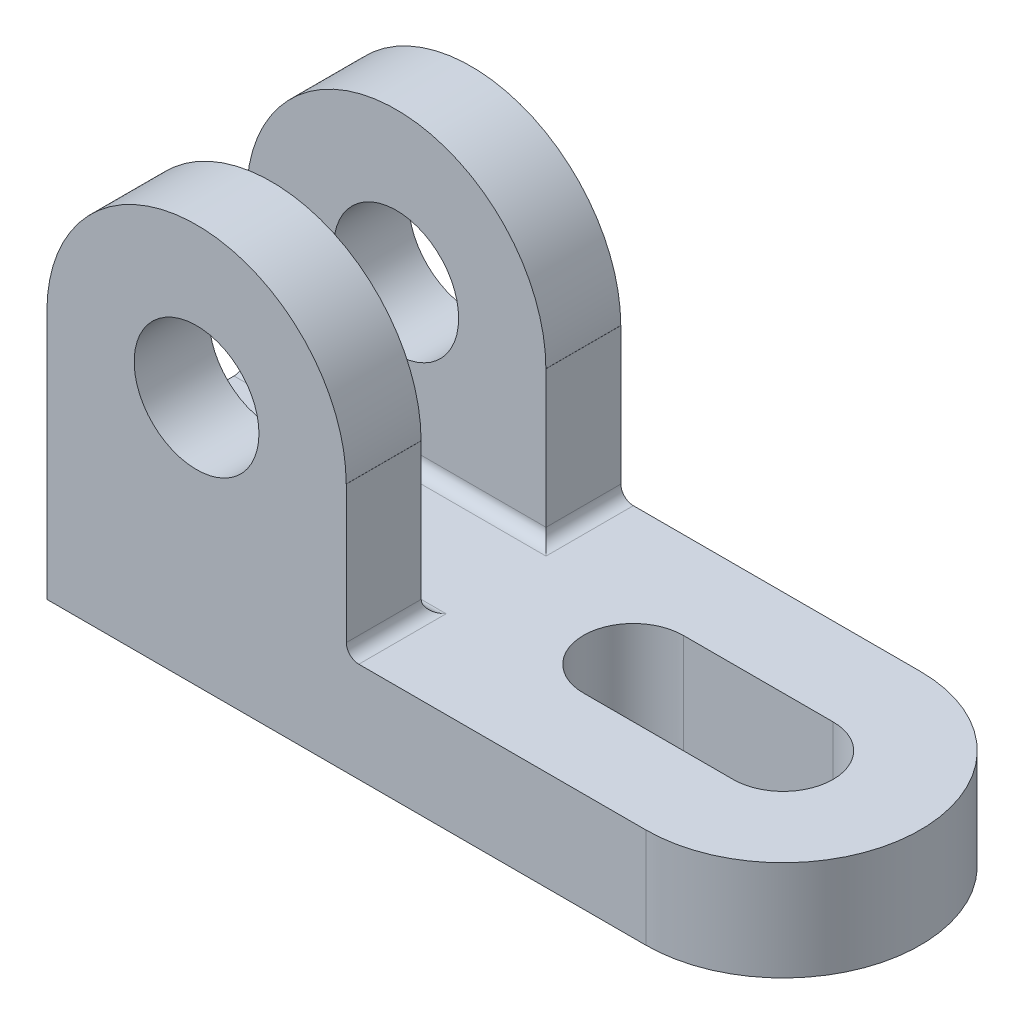
SolidWorks part; units mm, degrees
ref_plane "Front Plane" through (0, 0, 0) normal (0, 0, 1) x (1, 0, 0)
ref_plane "Top Plane" through (0, 0, 0) normal (0, 1, 0) x (1, 0, 0)
ref_plane "Right Plane" through (0, 0, 0) normal (1, 0, 0) x (0, 0, -1)
sketch "Sketch3" plane through (0, 0, 0) normal (0, 1, 0) x (1, 0, 0)
  line L1 (59, -22) -> (-59, -22)
  line L2 (59, -22) -> (59, 22)
  line L3 (59, 22) -> (-59, 22)
  line L4 (-59, -22) -> (-59, 22)
  line L5 (59, -22) -> (-59, 22) construction
  line L6 (59, 22) -> (-59, -22) construction
  circle A0 centre (37, 0) radius 22
  point P0 (0, 0)
  dimension "D1" = 118
  dimension "D2" = 44
extrude "Boss-Extrude1" add sketch "Sketch3" along normal blind 16 contours A0 L3 L4 L1 | A0
sketch "Sketch4" plane through (0, 16, 0) normal (0, 1, 0) x (1, 0, 0)
  line L0 (37, 0) -> (13, 0) construction
  line L1 (37, -8) -> (13, -8)
  line L2 (37, 8) -> (13, 8)
  arc A0 (37, -8) -> (37, 8) centre (37, 0) ccw
  arc A1 (13, 8) -> (13, -8) centre (13, 0) ccw
  point P4 (25, 0)
  dimension "D1" = 12
  dimension "D2" = 8
extrude "Cut-Extrude1" cut sketch "Sketch4" against normal blind 16
sketch "Sketch5" plane through (0, 0, 22) normal (0, 0, 1) x (1, 0, 0)
  line L0 (37, 0) -> (-59, 0) construction
  line L1 (-59, 16) -> (-11, 16)
  line L2 (-59, 16) -> (-59, 40)
  line L3 (-59, 40) -> (-11, 40)
  line L4 (-11, 16) -> (-11, 40)
  circle A0 centre (-35, 40) radius 23.9814
  circle A1 centre (-35, 40) radius 10
  line M7 (37, 16) -> (-59, 16)
  dimension "D3" = 20
  dimension "D1" = 48
  dimension "D2" = 40
extrude "Boss-Extrude2" add sketch "Sketch5" against normal blind 12 contours A0 L3 L2 L4 M7 | A1 L3 A0 | A1 L3 A0
mirror "Mirror1" about plane through (0, 0, 0) normal (0, 0, 1) of "Boss-Extrude2"
fillet "Fillet1" radius 2 4 edges at (-35, 16, -10) (-11, 16, -16) (-35, 16, 10) (-11, 16, 16)
